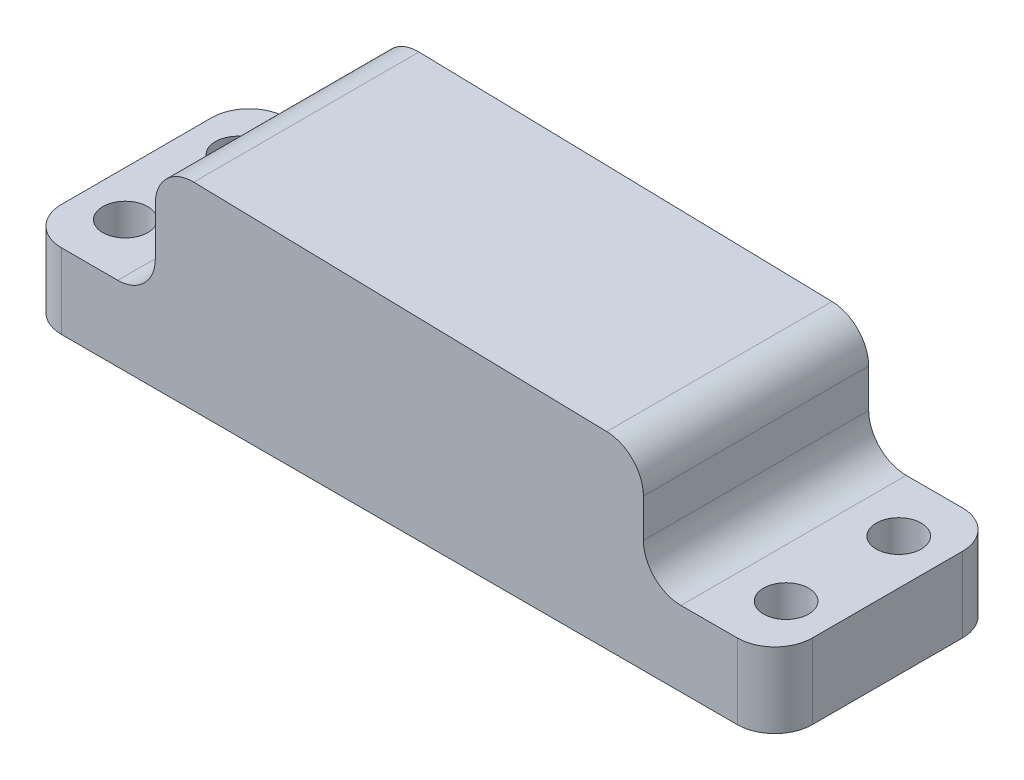
SolidWorks part; units mm, degrees
material "1023 Carbon Steel Sheet (SS)"
ref_plane "Front Plane" through (0, 0, 0) normal (0, 0, 1) x (1, 0, 0)
ref_plane "Top Plane" through (0, 0, 0) normal (0, 1, 0) x (1, 0, 0)
ref_plane "Right Plane" through (0, 0, 0) normal (1, 0, 0) x (0, 0, -1)
sketch "Sketch1" plane through (0, 0, 0) normal (0, 0, 1) x (1, 0, 0)
  line L0 (0, 0) -> (0, 20)
  line L1 (0, 20) -> (35, 20)
  line L2 (35, 20) -> (35, 53)
  line L3 (35, 53) -> (165, 50)
  line L4 (165, 50) -> (165, 20)
  line L5 (165, 20) -> (200, 20)
  line L6 (200, 20) -> (200, 0)
  line L7 (200, 0) -> (0, 0)
  dimension "D1" = 200
  dimension "D2" = 53
  dimension "D3" = 50
  dimension "D4" = 130
  dimension "D5" = 35
  dimension "D6" = 20
extrude "Boss-Extrude1" add sketch "Sketch1" along normal blind 60 contours L7 L0 L1 L2 L3 L4 L5 L6
ref_plane "Plane2" through (0, 0, 30) normal (0, 0, 1) x (1, 0, 0)
sketch "Sketch4" plane through (0, 20, 0) normal (0, 1, 0) x (1, 0, 0)
  line L0 (12, 26.3939) -> (12, -100.7401) construction
  line L2 (0, -60) -> (0, 0) construction
  line L3 (-27.9921, -45) -> (30.8975, -45) construction
  line L4 (0, -60) -> (35, -60) construction
  dimension "D1" = 15
  dimension "D2" = 12
hole_wizard "CBORE for M5 Hex Head Bolt1" positions "Sketch5" profile "Sketch6" counterbore size "M5" standard "ISO" end condition through all
sketch "Sketch5" plane through (0, 20, 0) normal (0, 1, 0) x (1, 0, 0)
  line L0 (12, 26.3939) -> (12, -100.7401) construction
  line L1 (-27.9921, -45) -> (30.8975, -45) construction
  point P0 (12, -45)
sketch "Sketch6" plane through (12, 20, 45) normal (1, 0, 0) x (0, 0, 1)
  line L0 (0, 0) -> (0, 20)
  line L1 (0, 20) -> (4, 20)
  line L3 (4, 20) -> (4, 10)
  line L4 (4, 10) -> (6, 10)
  line L5 (6, 10) -> (6, 0)
  line L7 (6, 0) -> (0, 0)
  line L11 (0, -6.35) -> (0, 107.95) construction
  dimension "Thru Hole Dia." = 8
  dimension "Thru Hole Depth" = 20
  dimension "C'Bore Dia." = 12
  dimension "C'Bore Depth" = 10
mirror "Mirror1" about plane through (0, 0, 30) normal (0, 0, 1) of "CBORE for M5 Hex Head Bolt1"
ref_plane "Plane3" through (100, 0, 0) normal (1, 0, 0) x (0, 0, -1)
mirror "Mirror2" about plane through (100, 0, 0) normal (1, 0, 0) of "Mirror1", "CBORE for M5 Hex Head Bolt1"
fillet "Fillet1" radius 10 4 edges at (165, 20, 30) (165, 50, 30) (35, 20, 30) (35, 53, 30)
fillet "Fillet2" radius 10 4 edges at (0, 10, 0) (0, 10, 60) (200, 10, 60) (200, 10, 0)
